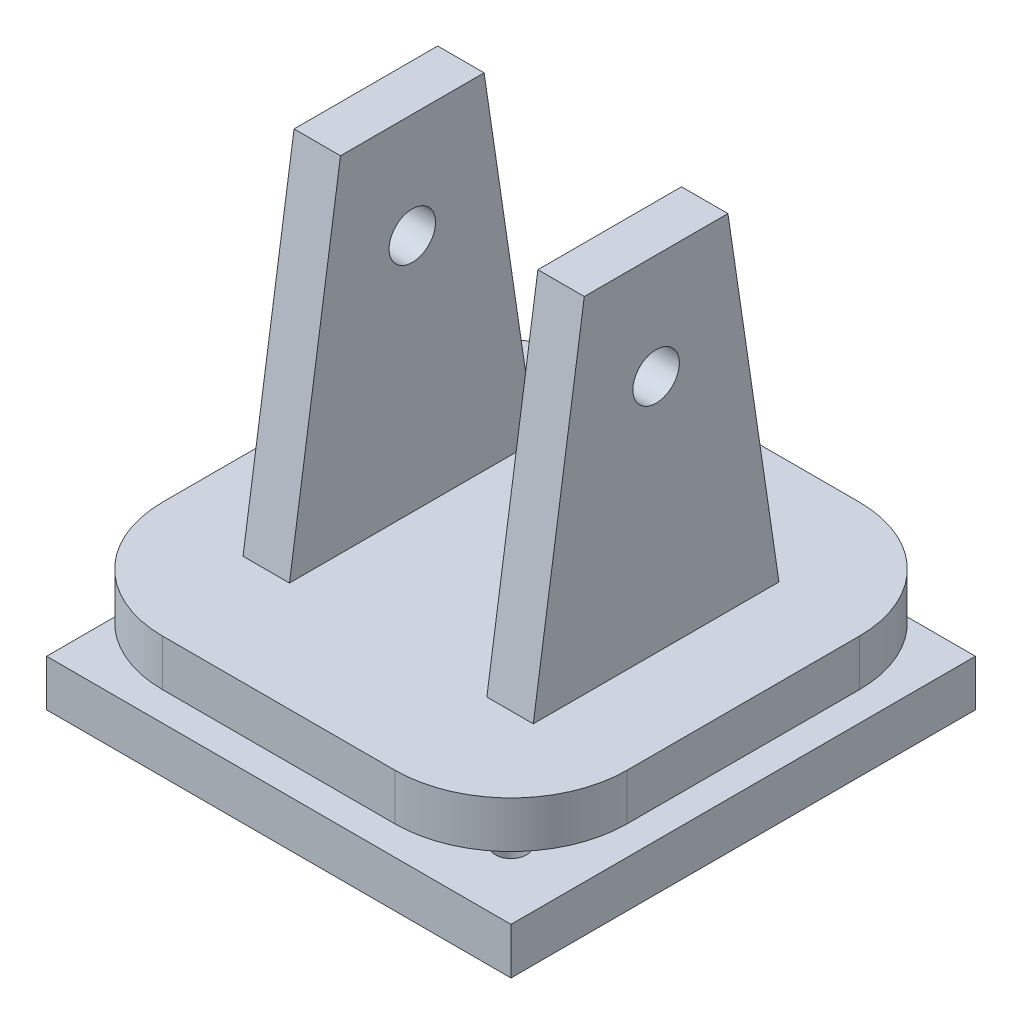
SolidWorks part; units mm, degrees
ref_plane "Front Plane" through (0, 0, 0) normal (0, 0, 1) x (1, 0, 0)
ref_plane "Top Plane" through (0, 0, 0) normal (0, 1, 0) x (1, 0, 0)
ref_plane "Right Plane" through (0, 0, 0) normal (1, 0, 0) x (0, 0, -1)
sketch "Sketch1" plane through (0, 0, 0) normal (0, 1, 0) x (1, 0, 0)
  line L1 (-40, 40) -> (40, 40)
  line L2 (-40, 40) -> (-40, -40)
  line L3 (-40, -40) -> (40, -40)
  line L4 (40, 40) -> (40, -40)
  line L5 (-40, 40) -> (40, -40) construction
  line L6 (-40, -40) -> (40, 40) construction
  point P0 (0, 0)
  dimension "D1" = 80
  dimension "D2" = 80
extrude "Boss-Extrude1" add sketch "Sketch1" along normal blind 8
sketch "Sketch2" plane through (0, 8, 0) normal (0, 1, 0) x (1, 0, 0)
  point P14 (0, 0)
ref_plane "Plane1" through (-25, 0, 0) normal (1, 0, 0) x (0, 0, -1)
sketch "Sketch4" plane through (-25, 0, 0) normal (1, 0, 0) x (0, 0, -1)
  line L0 (-21.1611, 8) -> (-12.3704, 67.3525)
  line L1 (-40, 8) -> (40, 8) construction
  line L2 (0, 84.8715) -> (0, -34.2595) construction
  line L3 (21.1611, 8) -> (12.3704, 67.3525)
  line L4 (-12.3704, 67.3525) -> (12.3704, 67.3525)
  line L5 (-21.1611, 8) -> (21.1611, 8)
  dimension "D1" = 60
extrude "Boss-Extrude2" add sketch "Sketch4" along normal blind 8
mirror "Mirror1" about plane through (0, 0, 0) normal (1, 0, 0) of "Boss-Extrude2"
sketch "Sketch5" plane through (25, 0, 0) normal (1, 0, 0) x (0, 0, -1)
  circle A0 centre (0, 49.2509) radius 4
  dimension "D1" = 8
extrude "Cut-Extrude2" cut sketch "Sketch5" against normal blind 85
sketch "Sketch6" plane through (0, 0, 0) normal (0, -1, 0) x (1, 0, 0)
  circle A0 centre (0, 0) radius 15
  dimension "D1" = 30
extrude "Boss-Extrude3" add sketch "Sketch6" along normal blind 5
sketch "Sketch7" plane through (0, -5, 0) normal (0, -1, 0) x (1, 0, 0)
  line L1 (-40, 40) -> (40, 40)
  line L2 (-40, 40) -> (-40, -40)
  line L3 (-40, -40) -> (40, -40)
  line L4 (40, 40) -> (40, -40)
  line L5 (-40, 40) -> (40, -40) construction
  line L6 (-40, -40) -> (40, 40) construction
  circle A0 centre (-28.2843, 28.2843) radius 2.6882
  circle A1 centre (28.2843, 28.2843) radius 2.6882
  circle A2 centre (28.2843, -28.2843) radius 2.6882
  circle A3 centre (-28.2843, -28.2843) radius 2.6882
  point P0 (0, 0)
  point P18 (0, 0)
  dimension "D1" = 40
  dimension "D2" = 4
extrude "Boss-Extrude4" add sketch "Sketch7" along normal blind 8
fillet "Fillet1" radius 20 1 edges at (-40, 4, -40)
fillet "Fillet2" radius 20 3 edges at (40, 4, -40) (40, 4, 40) (-40, 4, 40)
